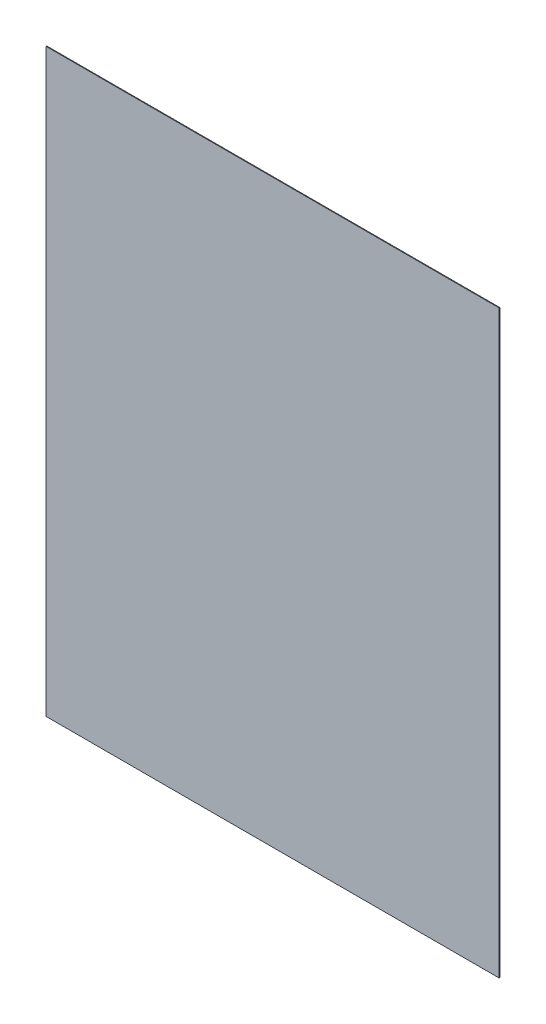
SolidWorks part; units mm, degrees
ref_plane "Front Plane" through (0, 0, 0) normal (0, 0, 1) x (1, 0, 0)
ref_plane "Top Plane" through (0, 0, 0) normal (0, 1, 0) x (1, 0, 0)
ref_plane "Right Plane" through (0, 0, 0) normal (1, 0, 0) x (0, 0, -1)
sketch "Croquis1" plane through (0, 0, 0) normal (0, 0, 1) x (1, 0, 0)
  line L1 (-323.895, -415) -> (323.895, -415)
  line L2 (-323.895, -415) -> (-323.895, 415)
  line L3 (-323.895, 415) -> (323.895, 415)
  line L4 (323.895, -415) -> (323.895, 415)
  line L5 (-323.895, -415) -> (323.895, 415) construction
  line L6 (-323.895, 415) -> (323.895, -415) construction
  point P0 (0, 0)
  dimension "D1" = 647.79
  dimension "D2" = 830
extrude "Saliente-Extruir1" add sketch "Croquis1" along normal blind 1
